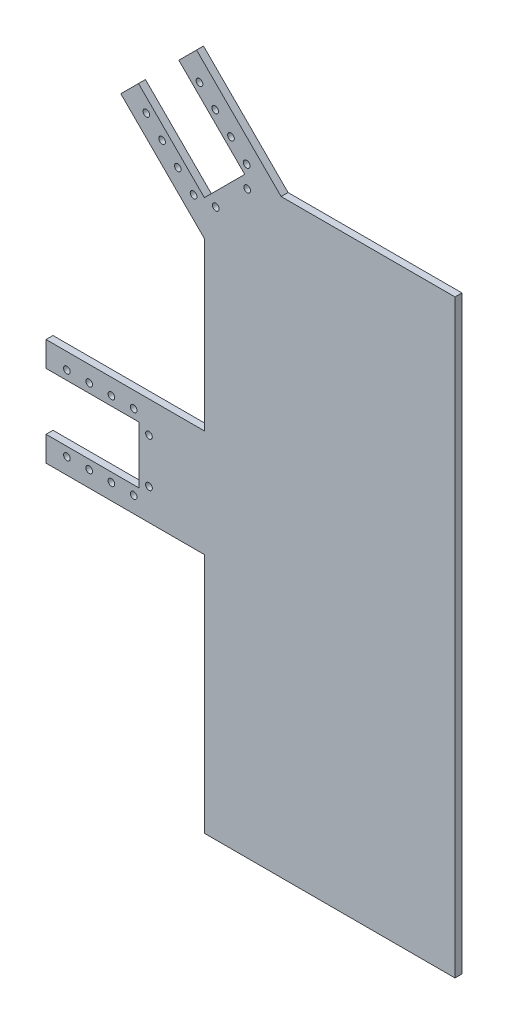
SolidWorks part; units mm, degrees
ref_plane "Plan de face" through (0, 0, 0) normal (0, 0, 1) x (1, 0, 0)
ref_plane "Plan de dessus" through (0, 0, 0) normal (0, 1, 0) x (1, 0, 0)
ref_plane "Plan de droite" through (0, 0, 0) normal (1, 0, 0) x (0, 0, -1)
sketch "Esquisse1" plane through (0, 0, 0) normal (0, 0, 1) x (1, 0, 0)
  line L1 (45, -106) -> (-45, -106)
  line L2 (45, -106) -> (45, 106)
  line L3 (45, 106) -> (-45, 106)
  line L4 (-45, -106) -> (-45, 106)
  line L5 (45, -106) -> (-45, 106) construction
  line L6 (45, 106) -> (-45, -106) construction
  point P0 (0, 0)
  dimension "D1" = 90
  dimension "D2" = 212
extrude "Boss.-Extru.1" add sketch "Esquisse1" along normal blind 2.5
sketch "Esquisse2" plane through (0, 0, 2.5) normal (0, 0, 1) x (1, 0, 0)
  line L0 (-45, 106) -> (-45, -106) construction
  line L1 (-45, 19.25) -> (-102, 19.25)
  line L2 (-45, 19.25) -> (-45, -19.25)
  line L3 (-45, -19.25) -> (-102, -19.25)
  line L4 (-102, 19.25) -> (-102, -19.25)
  line L5 (-102, 19.25) -> (-45, -19.25) construction
  line L6 (-45, 19.25) -> (-102, -19.25) construction
  line L7 (-47.9056, 136.4056) -> (-75.1292, 109.182)
  line L8 (-47.9056, 136.4056) -> (0, 88.5)
  line L9 (-75.1292, 109.182) -> (-27.2236, 61.2764)
  line L10 (0, 88.5) -> (-27.2236, 61.2764)
  line L11 (-47.9056, 136.4056) -> (-27.2236, 61.2764) construction
  line L12 (-75.1292, 109.182) -> (0, 88.5) construction
  line L13 (45, 106) -> (-45, 106) construction
  line L14 (0, -1000) -> (0, 49000) construction
  line L15 (0, 106) -> (-17.5, 106)
  point P6 (-73.5, 0)
  point P7 (-37.5646, 98.841)
  line M1 (-45, 106) -> (-45, -106)
  line M4 (45, 106) -> (-45, 106)
  dimension "D1" = 57
  dimension "D2" = 38.5
  dimension "D3" = 135
  dimension "D4" = 38.5
  dimension "D5" = 35
  dimension "D6" = 43
extrude "Boss.-Extru.2" add sketch "Esquisse2" against normal up to surface (2.5 mm away) contours L7 L9 L8 M1 M4 | L1 L4 L3 M1 up to face at (0, 0, 0)
sketch "Esquisse3" plane through (0, 0, 2.5) normal (0, 0, 1) x (1, 0, 0)
  line L0 (-54.2696, 130.0416) -> (-68.7652, 115.5459)
  line L1 (-54.2696, 130.0416) -> (-30.5815, 106.3536)
  line L2 (-68.7652, 115.5459) -> (-45.0772, 91.8579)
  line L3 (-30.5815, 106.3536) -> (-45.0772, 91.8579)
  line L4 (-47.9056, 136.4056) -> (-75.1292, 109.182) construction
  line L5 (-102, 10.25) -> (-102, -10.25)
  line L6 (-102, 10.25) -> (-68.5, 10.25)
  line L7 (-102, -10.25) -> (-68.5, -10.25)
  line L8 (-68.5, 10.25) -> (-68.5, -10.25)
  line L9 (-102, 19.25) -> (-102, -19.25) construction
  line L11 (-47.9056, 136.4056) -> (-17.5, 106) construction
  line L14 (-45, 19.25) -> (-102, 19.25) construction
  dimension "D1" = 20.5
  dimension "D2" = 9
  dimension "D3" = 33.5
  dimension "D4" = 33.5
  dimension "D5" = 9
  dimension "D6" = 20.5
extrude "Enlèv. mat.-Extru.1" cut sketch "Esquisse3" against normal up to next
sketch "Esquisse4" plane through (0, 0, 2.5) normal (0, 0, 1) x (1, 0, 0)
  line L0 (-68.5, -10.25) -> (-68.5, 10.25) construction
  line L1 (-102, -10.25) -> (-68.5, -10.25) construction
  line L2 (-45.0772, 91.8579) -> (-30.5815, 106.3536) construction
  line L3 (-68.7652, 115.5459) -> (-45.0772, 91.8579) construction
  line L4 (-65.9368, 107.7678) -> (35289.4022, -35247.5713) construction
  line L5 (0, -1000) -> (0, 49000) construction
  line L6 (-46.8449, 126.8597) -> (35308.4941, -35228.4794) construction
  line L7 (-41.0113, 90.974) -> (-29.6976, 102.2877) construction
  point P0 (-65, -8)
  point P1 (-70.5, -13.5)
  point P6 (-70.5, 13.5)
  point P7 (-48.9663, 90.7972)
  point P8 (-78.5, -13.5)
  point P9 (-78.5, 13.5)
  point P10 (-86.5, -13.5)
  point P11 (-94.5, -13.5)
  point P12 (-65, 8)
  point P13 (-86.5, 13.5)
  point P14 (-94.5, 13.5)
  point P15 (-41.0113, 90.974)
  point P20 (-54.6231, 96.4541)
  point P22 (-60.28, 102.1109)
  point P23 (-65.9368, 107.7678)
  point P26 (-29.8744, 109.8891)
  point P30 (-35.5312, 115.5459)
  point P31 (-41.1881, 121.2028)
  point P32 (-46.8449, 126.8597)
  point P36 (-29.6976, 102.2877)
  dimension "D1" = 3.5
  dimension "D2" = 3.25
  dimension "D3" = 2
  dimension "D4" = 2.25
  dimension "D7" = 16
  dimension "D8" = 8
  dimension "D10" = 27
  dimension "D11" = 3.5
  dimension "D12" = 2.25
  dimension "D13" = 3.5
  dimension "D14" = 2
  dimension "D16" = 8
  dimension "D17" = 45
  dimension "D19" = 27
  dimension "D20" = 2
  dimension "D22" = 16
  dimension "D5" = 4
  dimension "D6" = 2
  dimension "D9" = 2
  dimension "D15" = 4
  dimension "D18" = 2
  dimension "D21" = 2
hole_wizard "Dégagement M21" positions "Esquisse6" profile "Esquisse5" hole size "M2" standard "Iso" end condition through all
sketch "Esquisse6" plane through (0, 0, 2.5) normal (0, 0, 1) x (1, 0, 0)
  point P0 (-94.5, -13.5)
  point P3 (-86.5, -13.5)
  point P6 (-78.5, -13.5)
  point P9 (-70.5, -13.5)
  point P12 (-65, -8)
  point P15 (-65, 8)
  point P18 (-70.5, 13.5)
  point P21 (-78.5, 13.5)
  point P24 (-86.5, 13.5)
  point P27 (-94.5, 13.5)
  point P30 (-41.0113, 90.974)
  point P33 (-29.6976, 102.2877)
  point P36 (-29.8744, 109.8891)
  point P39 (-35.5312, 115.5459)
  point P42 (-41.1881, 121.2028)
  point P45 (-46.8449, 126.8597)
  point P48 (-65.9368, 107.7678)
  point P51 (-60.28, 102.1109)
  point P54 (-54.6231, 96.4541)
  point P57 (-48.9663, 90.7972)
sketch "Esquisse5" plane through (-94.5, -13.5, 2.5) normal (1, 0, 0) x (0, -1, 0)
  line L0 (0, 0) -> (0, 2.5)
  line L1 (0, 2.5) -> (1.2, 2.5)
  line L2 (1.2, 2.5) -> (1.2, 0)
  line L5 (1.2, 0) -> (0, 0)
  line L11 (0, -6.35) -> (0, 107.95) construction
  dimension "Diamètre du perçage jusqu'au prochain" = 2.4
  dimension "Profondeur du perçage jusqu'au prochain" = 2.5
